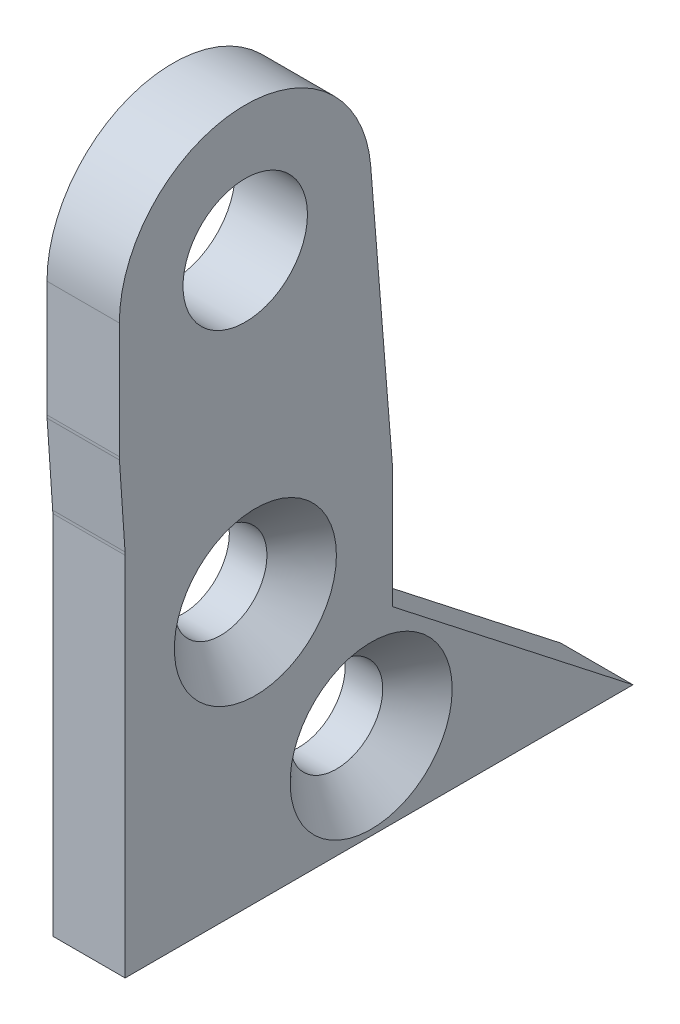
SolidWorks part; units mm, degrees
ref_plane "Front Plane" through (0, 0, 0) normal (0, 0, 1) x (1, 0, 0)
ref_plane "Top Plane" through (0, 0, 0) normal (0, 1, 0) x (1, 0, 0)
ref_plane "Right Plane" through (0, 0, 0) normal (1, 0, 0) x (0, 0, -1)
sketch "Sketch1" plane through (0, 0, 0) normal (1, 0, 0) x (0, 0, -1)
  line L0 (-4.35, 0) -> (-4.35, -4)
  line L1 (-4.15, -20.2) -> (14.85, -20.2)
  line L3 (14.85, -20.2) -> (5.3939, -12.8121)
  line L4 (5.3939, -12.8121) -> (4.336, 0.3485)
  line L5 (-161.4, -23) -> (38.6, -23) construction
  line L6 (-4.3466, -4.1015) -> (-4.1534, -6.9493)
  line L7 (-4.15, -7.0508) -> (-4.15, -20.2)
  circle A0 centre (0, 0) radius 2.15
  arc A1 (4.336, 0.3485) -> (-4.35, 0) centre (0, 0) ccw
  arc A2 (-4.35, -4) -> (-4.3466, -4.1015) centre (-2.85, -4) ccw
  arc A3 (-4.15, -7.0508) -> (-4.1534, -6.9493) centre (-5.65, -7.0508) ccw
  point P16 (-4.15, -7)
  dimension "D1" = 4.3
  dimension "D2" = 8.7
  dimension "D8" = 20.2
  dimension "D3" = 1.5
  dimension "D4" = 13.2
  dimension "D10" = 1.5
  dimension "D5" = 38
  dimension "D6" = 12
  dimension "D7" = 2.8
  dimension "D9" = 0.2
  dimension "D11" = 4
  dimension "D12" = 19
extrude "Boss-Extrude1" add sketch "Sketch1" along normal mid plane 2.5
sketch "Sketch3" plane through (1.25, 0, 0) normal (1, 0, 0) x (0, 0, -1)
  line L0 (-4.15, -20.2) -> (14.85, -20.2) construction
  line L1 (14.85, -20.2) -> (5.3939, -12.8121) construction
  line L2 (-4.15, -20.2) -> (14.85, -20.2)
  line L3 (14.85, -20.2) -> (5.3939, -12.8121)
  line L4 (-4.15, -19.7) -> (13.3979, -19.7)
  line L5 (13.3979, -19.7) -> (5.086, -13.2061)
  line L6 (5.086, -13.2061) -> (5.086, -8.9824)
  line L7 (5.3939, -12.8121) -> (4.336, 0.3485) construction
  line L8 (5.086, -8.9824) -> (5.3939, -12.8121)
  line L9 (-4.15, -19.7) -> (-4.15, -20.2)
  line L10 (-4.15, -7.0508) -> (-4.15, -20.2) construction
  circle A0 centre (0.35, -10.7) radius 1.6
  circle A1 centre (4.35, -16.7) radius 1.6
  dimension "D2" = 3.2
  dimension "D5" = 4.5
  dimension "D6" = 9
  dimension "D3" = 3
  dimension "D4" = 8.5
  dimension "D1" = 0.5
extrude "Cut-Extrude1" cut sketch "Sketch3" against normal through all
chamfer "Chamfer1" distance 1.2 angle 45 2 edges at (1.25, -16.7, -5.95) (1.25, -10.7, -1.95)
